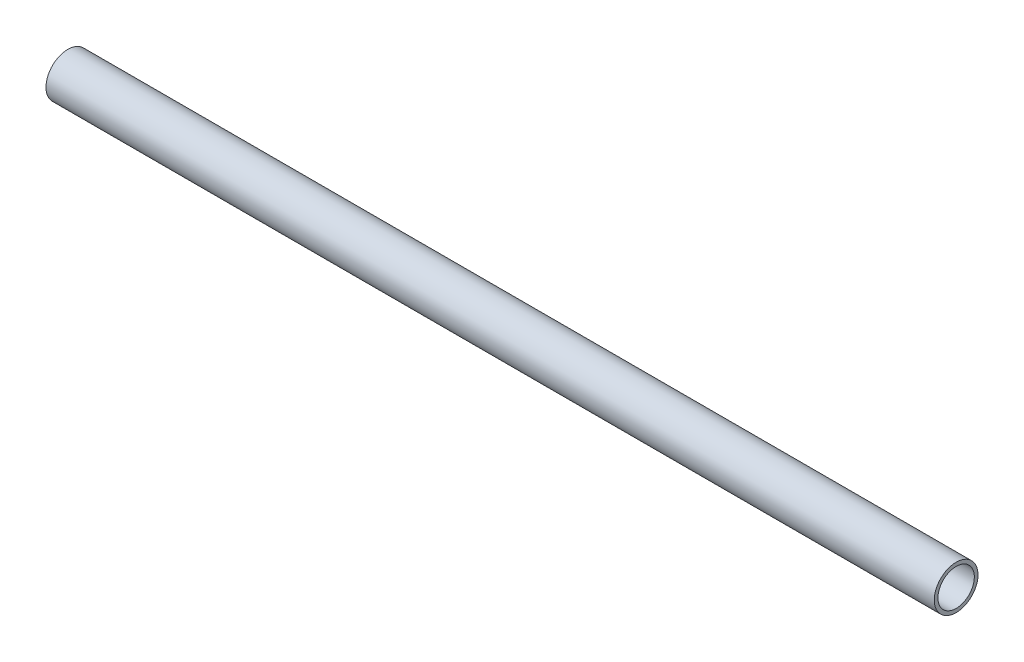
SolidWorks part; units mm, degrees
ref_plane "Front Plane" through (0, 0, 0) normal (0, 0, 1) x (1, 0, 0)
ref_plane "Top Plane" through (0, 0, 0) normal (0, 1, 0) x (1, 0, 0)
ref_plane "Right Plane" through (0, 0, 0) normal (1, 0, 0) x (0, 0, -1)
sketch "Sketch1" plane through (0, 0, 0) normal (0, 0, 1) x (1, 0, 0)
  line L0 (17.6222, 1527.5128) -> (275.5537, 1527.5128)
  point P2 (17.6222, 1527.5128)
other "Pipe 0.5 SCH 40(1)"
ref_plane "Plane1" through (17.6222, 1527.5128, 0) normal (1, 0, 0) x (0, 1, 0)
sketch "Sketch11" plane through (17.6222, 1527.5128, 0) normal (1, 0, 0) x (0, 1, 0)
  circle A0 centre (0, 0) radius 5.2832
  circle A1 centre (0, 0) radius 6.35
  point P5 (0, 0)
  dimension "D1" = 12.7
  dimension "D2" = 10.5664
